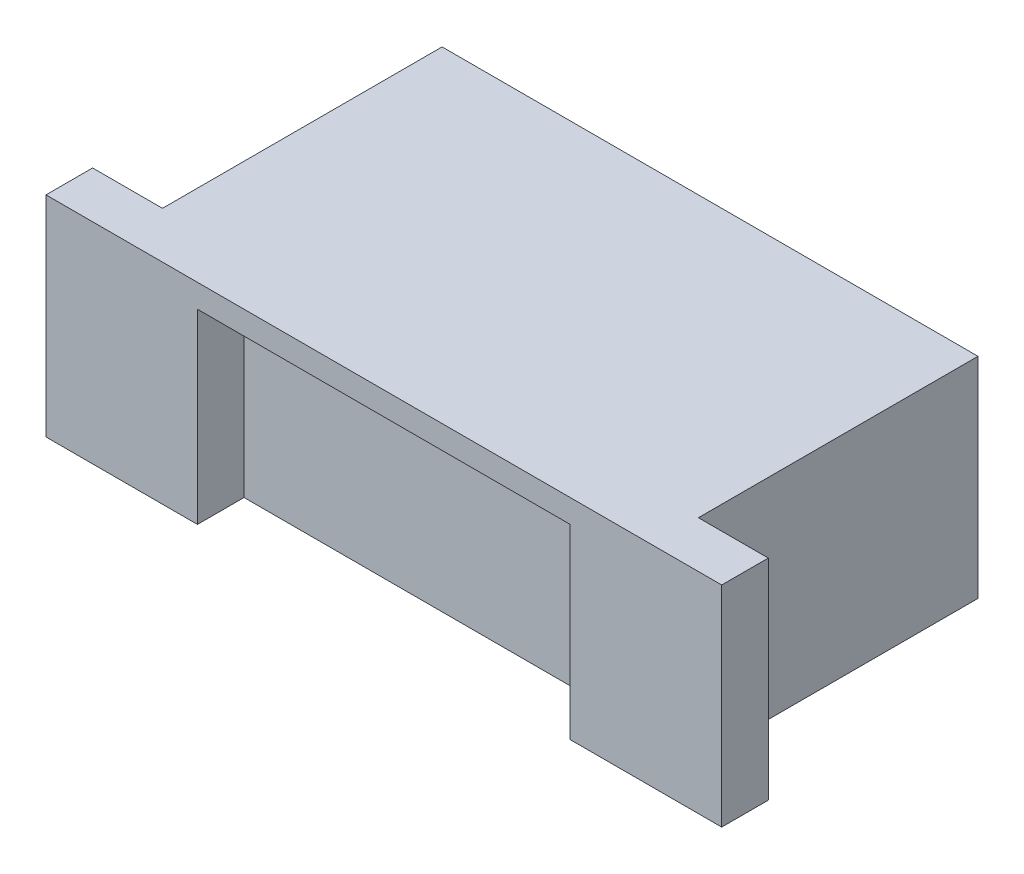
SolidWorks part; units mm, degrees
ref_plane "Płaszczyzna przednia" through (0, 0, 0) normal (0, 0, 1) x (1, 0, 0)
ref_plane "Płaszczyzna górna" through (0, 0, 0) normal (0, 1, 0) x (1, 0, 0)
ref_plane "Płaszczyzna prawa" through (0, 0, 0) normal (1, 0, 0) x (0, 0, -1)
sketch "Sketch1" plane through (0, 0, 0) normal (0, 1, 0) x (1, 0, 0)
  line L0 (0, 0) -> (7.25, 0)
  line L1 (7.25, 0) -> (7.25, 0.5)
  line L2 (7.25, 0.5) -> (6.5, 0.5)
  line L3 (6.5, 0.5) -> (6.5, 3.5)
  line L4 (6.5, 3.5) -> (0.75, 3.5)
  line L5 (0.75, 3.5) -> (0.75, 0.5)
  line L6 (0.75, 0.5) -> (0, 0.5)
  line L7 (0, 0.5) -> (0, 0)
  line L8 (3.625, 3.5) -> (3.625, 0) construction
  dimension "D1" = 0.5
  dimension "D2" = 7.25
  dimension "D3" = 5.75
  dimension "D4" = 3
extrude "Boss-Extrude1" add sketch "Sketch1" along normal blind 2.25
sketch "Sketch2" plane through (0, 0, 0) normal (0, 0, 1) x (1, 0, 0)
  line L0 (0, 0) -> (7.25, 0) construction
  line L1 (1.625, 0) -> (5.625, 0)
  line L2 (1.625, 0) -> (1.625, 2)
  line L3 (1.625, 2) -> (5.625, 2)
  line L4 (5.625, 0) -> (5.625, 2)
  line L5 (3.625, 2) -> (3.625, 0) construction
  dimension "D1" = 2
  dimension "D2" = 4
extrude "Cut-Extrude1" cut sketch "Sketch2" against normal blind 0.5
